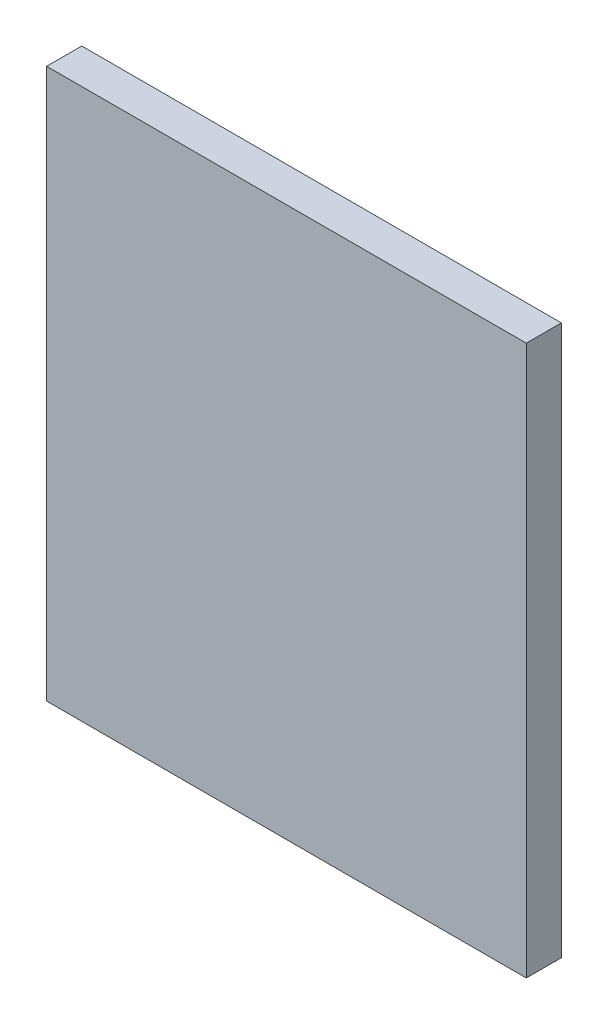
SolidWorks part; units mm, degrees
ref_plane "Front Plane" through (0, 0, 0) normal (0, 0, 1) x (1, 0, 0)
ref_plane "Top Plane" through (0, 0, 0) normal (0, 1, 0) x (1, 0, 0)
ref_plane "Right Plane" through (0, 0, 0) normal (1, 0, 0) x (0, 0, -1)
sketch "Sketch1" plane through (0, 0, 0) normal (0, 0, 1) x (1, 0, 0)
  line L1 (-162.6876, 313.4216) -> (247.3124, 313.4216)
  line L2 (-162.6876, 313.4216) -> (-162.6876, -156.5784)
  line L3 (-162.6876, -156.5784) -> (247.3124, -156.5784)
  line L4 (247.3124, 313.4216) -> (247.3124, -156.5784)
  dimension "D1" = 410
  dimension "D2" = 470
extrude "Boss-Extrude1" add sketch "Sketch1" along normal blind 30
